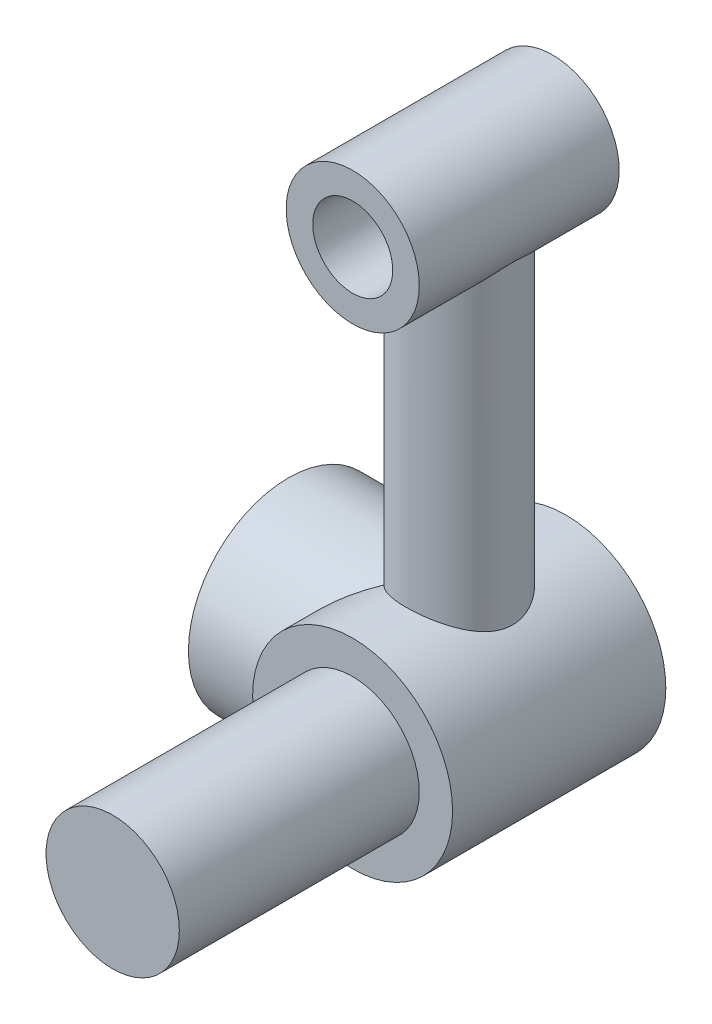
SolidWorks part; units mm, degrees
ref_plane "Front Plane" through (0, 0, 0) normal (0, 0, 1) x (1, 0, 0)
ref_plane "Top Plane" through (0, 0, 0) normal (0, 1, 0) x (1, 0, 0)
ref_plane "Right Plane" through (0, 0, 0) normal (1, 0, 0) x (0, 0, -1)
sketch "Sketch1" plane through (0, 0, 0) normal (0, 0, 1) x (1, 0, 0)
  circle A0 centre (-700, 1796) radius 50
extrude "Boss-Extrude1" add sketch "Sketch1" against normal blind 180
sketch "Sketch2" plane through (0, 0, -180) normal (0, 0, -1) x (-1, 0, 0)
  circle A0 centre (700, 1796) radius 75
  circle A1 centre (700, 1796) radius 50 construction
  dimension "D1" = 150
extrude "Boss-Extrude2" add sketch "Sketch2" along normal blind 160
ref_plane "Plane1" through (-700, 0, 0) normal (1, 0, 0) x (0, 0, -1)
sketch "Sketch3" plane through (-700, 0, 0) normal (1, 0, 0) x (0, 0, -1)
  line L0 (180, 1721) -> (340, 1721) construction
  circle A0 centre (260, 1796) radius 75
  dimension "D1" = 150
extrude "Boss-Extrude3" add sketch "Sketch3" against normal blind 128.18
ref_plane "Plane2" through (0, 1795, 0) normal (0, 1, 0) x (-1, 0, 0)
sketch "Sketch6" plane through (0, 1795, 0) normal (0, 1, 0) x (-1, 0, 0)
  line L1 (625, -180) -> (625, -340) construction
  line L2 (775, -180) -> (625, -180) construction
  line L3 (700, -180) -> (700, -260) construction
  line L4 (700, -260) -> (775, -335) construction
  line L5 (775, -185) -> (700, -260) construction
  line L6 (700, -260) -> (625, -260) construction
  circle A0 centre (700, -260) radius 40
  dimension "D1" = 80
extrude "Boss-Extrude6" add sketch "Sketch6" along normal blind 300
sketch "Sketch7" plane through (0, 0, -180) normal (0, 0, 1) x (1, 0, 0)
  line L0 (-660, 2095) -> (-740, 2095) construction
  circle A0 centre (-699.912, 2125) radius 30
  circle A1 centre (-699.912, 2125) radius 49.9296
  dimension "D1" = 60
extrude "Boss-Extrude7" add sketch "Sketch7" against normal blind 150
sketch "Sketch4" plane through (0, 1795, 0) normal (0, 1, 0) x (-1, 0, 0)
  line L0 (775, -180) -> (625, -180) construction
  line L1 (700, -180) -> (700, -260) construction
  line L2 (700, -260) -> (625, -260) construction
  line L3 (625, -180) -> (625, -340) construction
  circle A0 centre (700, -260) radius 40
  dimension "D1" = 80
extrude "Boss-Extrude4" [suppressed] add sketch "Sketch4" against normal blind 300
sketch "Sketch5" [suppressed] plane through (0, 0, -180) normal (0, 0, 1) x (1, 0, 0)
  line L0 (-740, 1495) -> (-660, 1495) construction
  circle A0 centre (-700, 1465) radius 30
  circle A1 centre (-700, 1465) radius 50
  dimension "D1" = 60
extrude "Boss-Extrude5" [suppressed] add sketch "Sketch5" against normal blind 150
